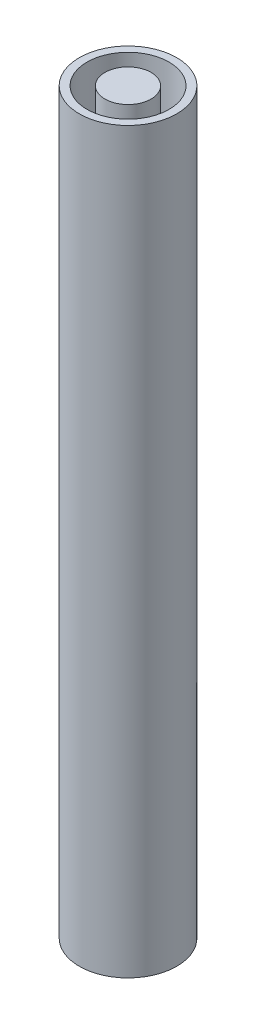
SolidWorks part; units mm, degrees
ref_plane "Front Plane" through (0, 0, 0) normal (0, 0, 1) x (1, 0, 0)
ref_plane "Top Plane" through (0, 0, 0) normal (0, 1, 0) x (1, 0, 0)
ref_plane "Right Plane" through (0, 0, 0) normal (1, 0, 0) x (0, 0, -1)
sketch "Sketch1" plane through (0, 0, 0) normal (0, 0, 1) x (1, 0, 0)
  line L0 (0, 0) -> (0, -161.7328) construction
  line L2 (28.575, 0) -> (31.75, 0) construction
  line L3 (28.575, 0) -> (28.575, 914.4) construction
  line L4 (28.575, 914.4) -> (31.75, 914.4) construction
  line L5 (31.75, 0) -> (31.75, 914.4) construction
  line L6 (47.625, 0) -> (50.8, 0) construction
  line L7 (47.625, 0) -> (47.625, 914.4) construction
  line L8 (47.625, 914.4) -> (50.8, 914.4) construction
  line L9 (50.8, 0) -> (50.8, 914.4) construction
  line L10 (60.325, 0) -> (63.5, 0) construction
  line L11 (60.325, 0) -> (60.325, 914.4) construction
  line L12 (60.325, 914.4) -> (63.5, 914.4) construction
  line L13 (63.5, 0) -> (63.5, 914.4) construction
  line L14 (28.575, 0) -> (0, 0)
  line L15 (28.575, 0) -> (28.575, 914.4)
  line L16 (28.575, 914.4) -> (0, 914.4)
  line L17 (0, 0) -> (0, 914.4)
  line L18 (50.8, 914.4) -> (60.325, 914.4)
  line L19 (50.8, 914.4) -> (50.8, 0)
  line L20 (50.8, 0) -> (60.325, 0)
  line L21 (60.325, 914.4) -> (60.325, 0)
  point P15 (0, -161.7328)
  dimension "D1" = 3.175
  dimension "D2" = 914.4
  dimension "D3" = 127
  dimension "D4" = 101.6
  dimension "D5" = 63.5
revolve "Revolve1" add sketch "Sketch1" angle 360 about L0
